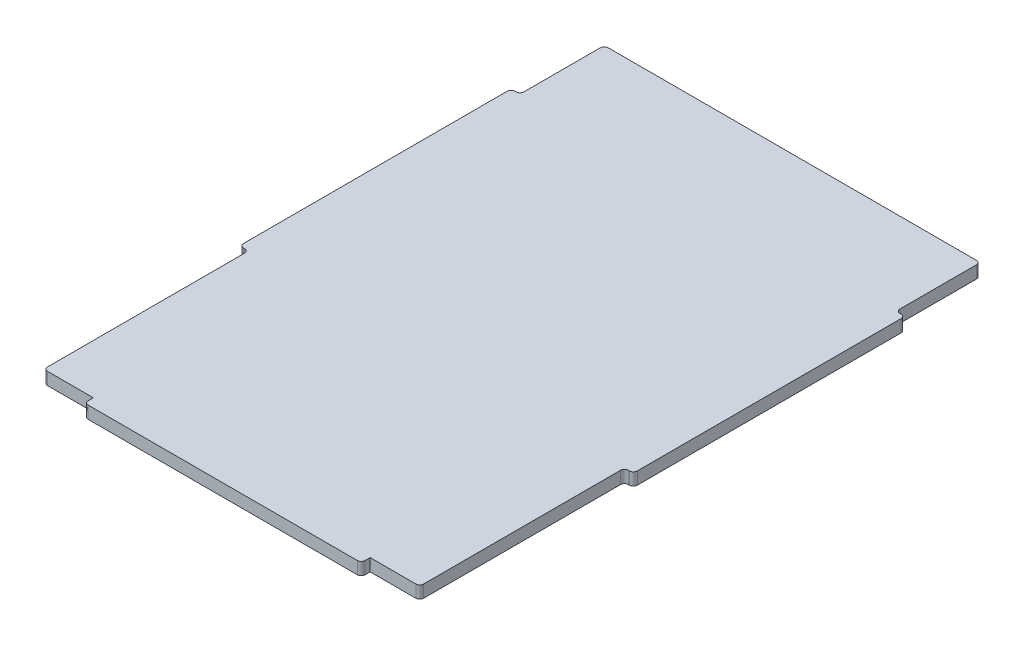
SolidWorks part; units mm, degrees
material "AISI 4130 Steel, annealed at 865C"
ref_plane "X-Y Datum" through (0, 0, 0) normal (0, 0, 1) x (1, 0, 0)
ref_plane "X-Z Datum" through (0, 0, 0) normal (0, 1, 0) x (1, 0, 0)
ref_plane "Y-Z Datum" through (0, 0, 0) normal (1, 0, 0) x (0, 0, -1)
sketch "Sketch1" plane through (0, 0, 0) normal (0, 1, 0) x (1, 0, 0)
  line L0 (83.6803, 0) -> (96.3803, 0)
  line L1 (0, 0) -> (12.7, 0)
  line L2 (0, 0) -> (0, 143.6878)
  line L3 (0, 143.6878) -> (96.3803, 143.6878)
  line L4 (96.3803, 0) -> (96.3803, 143.6878)
  line L5 (12.7, -2.286) -> (83.6803, -2.286)
  line L6 (12.7, -2.286) -> (12.7, 0)
  line L8 (83.6803, -2.286) -> (83.6803, 0)
  point P5 (48.1902, 0)
extrude "Boss-Extrude1" add sketch "Sketch1" along normal blind 3.175
sketch "Sketch2" plane through (0, 0, 0) normal (0, -1, 0) x (1, 0, 0)
  line L0 (0, -143.6878) -> (0, 0) construction
  line L1 (0, -52.4789) -> (-2.286, -52.4789)
  line L2 (0, -52.4789) -> (0, -122.095)
  line L3 (0, -122.095) -> (-2.286, -122.095)
  line L4 (-2.286, -52.4789) -> (-2.286, -122.095)
  line L5 (0, 0) -> (12.7, 0) construction
  line L6 (48.1901, 2.286) -> (48.1901, -20.3814) construction
  line L8 (96.3803, -122.095) -> (98.6663, -122.095)
  line L9 (98.6663, -52.4789) -> (98.6663, -122.095)
  line L10 (96.3803, -52.4789) -> (98.6663, -52.4789)
  line L11 (96.3803, -52.4789) -> (96.3803, -122.095)
  dimension "D1" = 52.4789
extrude "Boss-Extrude2" add sketch "Sketch2" against normal through all
fillet "Fillet1" radius 1 14 edges at (96.3803, 1.5875, -143.6878) (0, 1.5875, -143.6878) (0, 1.5875, -122.095) (-2.286, 1.5875, -122.095) (-2.286, 1.5875, -52.4789) (0, 1.5875, -52.4789) (0, 1.5875, 0) (12.7, 1.5875, 2.286) (83.6803, 1.5875, 2.286) (96.3803, 1.5875, 0) (96.3803, 1.5875, -52.4789) (98.6663, 1.5875, -52.4789) (98.6663, 1.5875, -122.095) (96.3803, 1.5875, -122.095)
